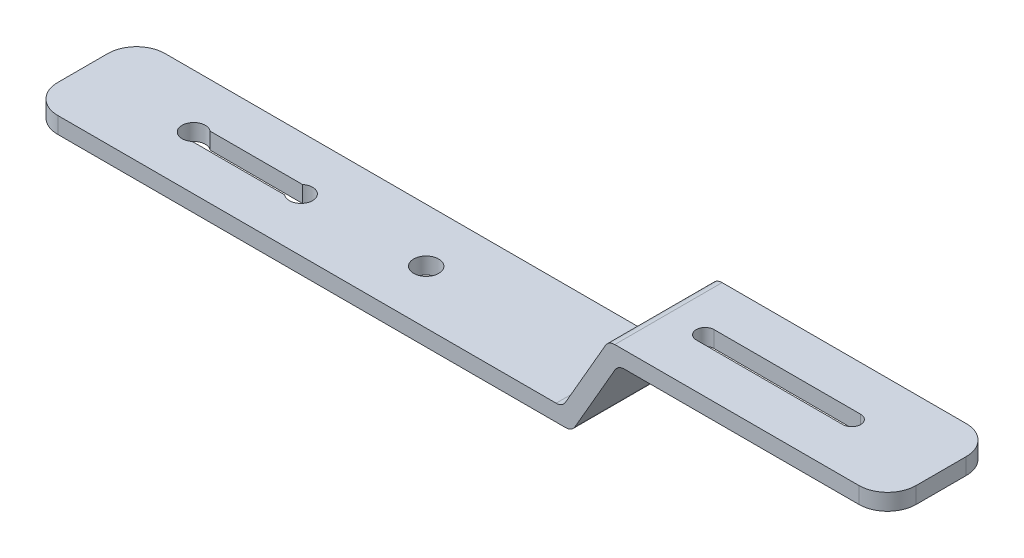
SolidWorks part; units mm, degrees
ref_plane "前基準面" through (0, 0, 0) normal (0, 0, 1) x (1, 0, 0)
ref_plane "上基準面" through (0, 0, 0) normal (0, 1, 0) x (1, 0, 0)
ref_plane "右基準面" through (0, 0, 0) normal (1, 0, 0) x (0, 0, -1)
sketch "草圖2" plane through (0, 0, 0) normal (0, 0, 1) x (1, 0, 0)
  line L0 (159.3811, 13.2486) -> (152.5981, 1.5)
  line L1 (159.3811, 13.2486) -> (163.7987, 20.9)
  line L2 (166.3967, 22.4) -> (240, 22.4)
  line L3 (240, 22.4) -> (240, 27)
  line L4 (159.3811, 13.2486) -> (127.3852, 31.7214) construction
  line L5 (147.3442, 4.6) -> (0, 4.6)
  line L6 (155.3974, 15.5486) -> (161.1429, 25.5)
  line L7 (163.7409, 27) -> (240, 27)
  line L8 (155.3974, 15.5486) -> (186.6139, -2.4743) construction
  line L9 (0, 4.6) -> (0, 0)
  line L10 (155.3974, 15.5486) -> (149.9423, 6.1)
  line L11 (150, 0) -> (0, 0)
  line L12 (0, 0) -> (33.2587, 0) construction
  arc A0 (152.5981, 1.5) -> (150, 0) centre (150, 3) cw
  arc A1 (161.1429, 25.5) -> (163.7409, 27) centre (163.7409, 24) cw
  arc A2 (163.7987, 20.9) -> (166.3967, 22.4) centre (166.3967, 19.4) cw
  arc A3 (149.9423, 6.1) -> (147.3442, 4.6) centre (147.3442, 7.6) cw
  dimension "D1" = 4.6
  dimension "D8" = 3
  dimension "D9" = 3
  dimension "D2" = 27
  dimension "D3" = 240
  dimension "D4" = 0
  dimension "D5" = 4.6
  dimension "D6" = 4.6
  dimension "D7" = 150
extrude "填料-伸長1" add sketch "草圖2" along normal mid plane 30
sketch "草圖3" plane through (0, 4.6, 0) normal (0, 1, 0) x (1, 0, 0)
  line L0 (0, -15) -> (0, 15) construction
  line L1 (0, 0) -> (199.4847, 0) construction
  line L2 (33.0767, 2.5) -> (58.9233, 2.5)
  line L3 (33.0767, -2.5) -> (58.9233, -2.5)
  line L4 (46, -7.9627) -> (46, -35.4246) construction
  arc A0 (33.0767, 2.5) -> (33.0767, -2.5) centre (31, 0) ccw
  arc A1 (58.9233, 2.5) -> (58.9233, -2.5) centre (61, 0) cw
  dimension "D1" = 31
  dimension "D3" = 5
  dimension "D4" = 15
  dimension "D2" = 6.5
extrude "除料-伸長1" cut sketch "草圖3" against normal through all
fillet "圓角1" radius 8 2 edges at (240, 24.7, -15) (240, 24.7, 15)
sketch "草圖4" plane through (0, 4.6, 0) normal (0, 1, 0) x (1, 0, 0)
  line L1 (96, 0) -> (119.691, 0) construction
  line L2 (0, -15) -> (0, 15) construction
  line L9 (147.3442, -15) -> (0, -15) construction
  line L10 (147.3442, 15) -> (0, 15) construction
  circle A0 centre (96, 0) radius 3.5
  dimension "D1" = 7
  dimension "D2" = 96
extrude "除料-伸長2" cut sketch "草圖4" against normal through all
sketch "草圖5" plane through (0, 27, 0) normal (0, 1, 0) x (1, 0, 0)
  line L0 (170.5679, 0) -> (232.3695, 0) construction
  line L2 (174, -2.5) -> (215, -2.5)
  line L3 (174, 2.5) -> (215, 2.5)
  line L5 (240, -7) -> (240, 7) construction
  line L6 (0, 2.5) -> (242.1694, 2.5) construction
  line L7 (0, 0) -> (242.1694, 0) construction
  line L8 (0, -2.5) -> (242.1694, -2.5) construction
  line L9 (232, -15) -> (163.7409, -15) construction
  line L10 (232, 15) -> (163.7409, 15) construction
  line L11 (240, -7) -> (240, 7) construction
  arc A0 (174, -2.5) -> (174, 2.5) centre (174, 0) cw
  arc A1 (215, 2.5) -> (215, -2.5) centre (215, 0) cw
  point P18 (240, 0)
  dimension "D4" = 25
  dimension "D3" = 66
  dimension "D1" = 2.5
  dimension "D2" = 2.5
extrude "除料-伸長3" cut sketch "草圖5" against normal through all
fillet "圓角2" radius 8 2 edges at (0, 2.3, 15) (0, 2.3, -15)
